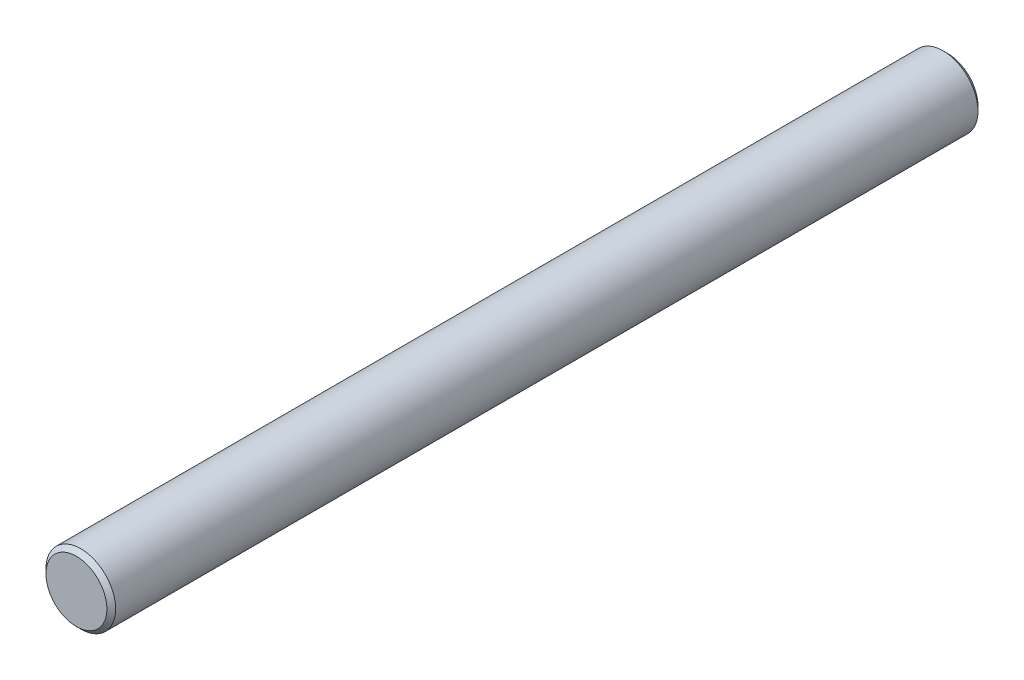
SolidWorks part; units mm, degrees
ref_plane "Front Plane" through (0, 0, 0) normal (0, 0, 1) x (1, 0, 0)
ref_plane "Top Plane" through (0, 0, 0) normal (0, 1, 0) x (1, 0, 0)
ref_plane "Right Plane" through (0, 0, 0) normal (1, 0, 0) x (0, 0, -1)
sketch "Sketch1" plane through (0, 0, 0) normal (0, 0, 1) x (1, 0, 0)
  circle A0 centre (0, 0) radius 4
extrude "Boss-Extrude1" add sketch "Sketch1" along normal blind 100
chamfer "Chamfer1" distance 0.5 angle 45 2 edges at (4, 0, 100) (4, 0, 0)
